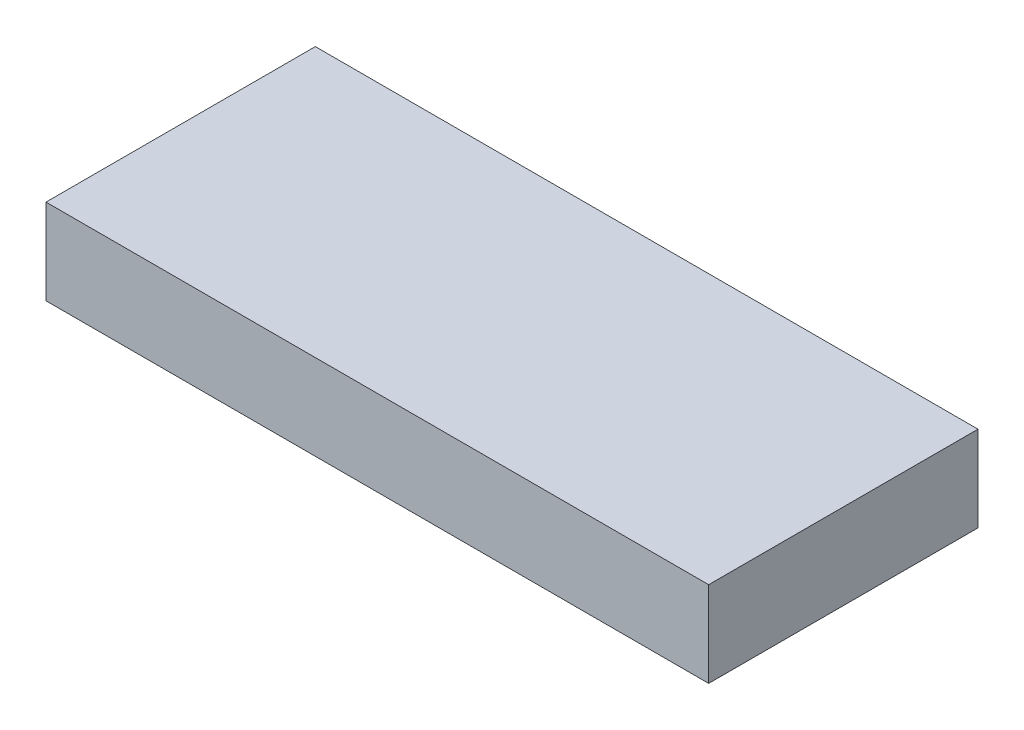
SolidWorks part; units mm, degrees
ref_plane "Front Plane" through (0, 0, 0) normal (0, 0, 1) x (1, 0, 0)
ref_plane "Top Plane" through (0, 0, 0) normal (0, 1, 0) x (1, 0, 0)
ref_plane "Right Plane" through (0, 0, 0) normal (1, 0, 0) x (0, 0, -1)
sketch "Sketch1" plane through (0, 0, 0) normal (0, 0, 1) x (1, 0, 0)
  line L1 (-26.9515, 16.2519) -> (4.0485, 16.2519)
  line L2 (-26.9515, 16.2519) -> (-26.9515, 12.2519)
  line L3 (-26.9515, 12.2519) -> (4.0485, 12.2519)
  line L4 (4.0485, 16.2519) -> (4.0485, 12.2519)
  dimension "D1" = 31
  dimension "D2" = 4
extrude "Boss-Extrude1" add sketch "Sketch1" along normal blind 12.6
